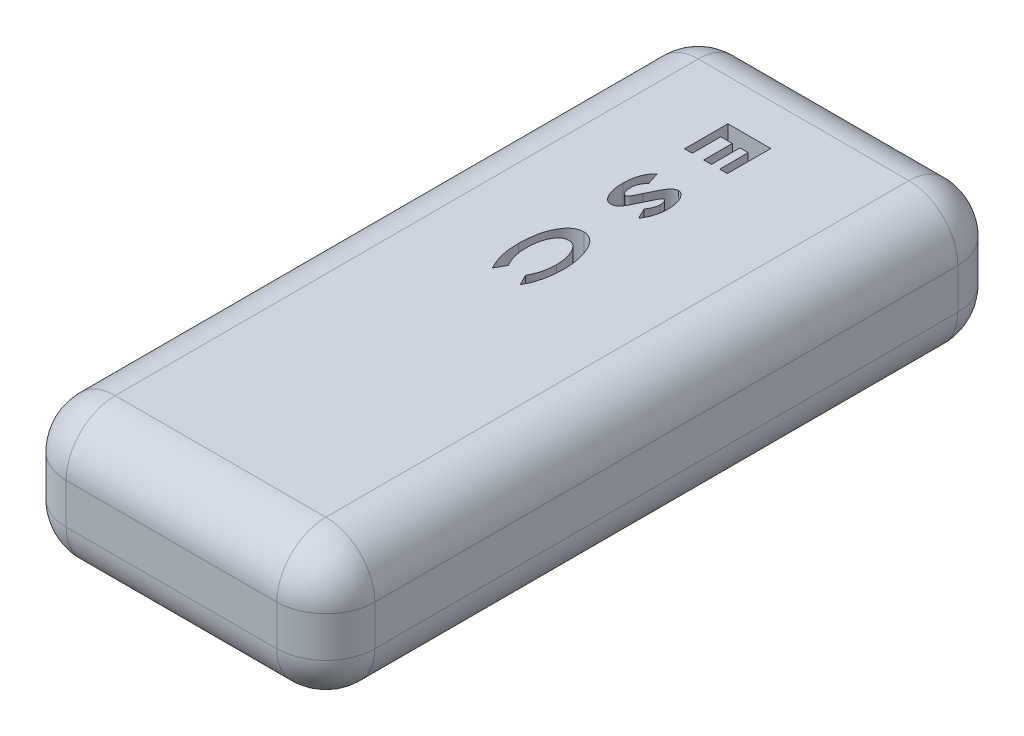
SolidWorks part; units mm, degrees
ref_plane "Front Plane" through (0, 0, 0) normal (0, 0, 1) x (1, 0, 0)
ref_plane "Top Plane" through (0, 0, 0) normal (0, 1, 0) x (1, 0, 0)
ref_plane "Right Plane" through (0, 0, 0) normal (1, 0, 0) x (0, 0, -1)
sketch "Sketch1" plane through (0, 0, 0) normal (0, 1, 0) x (1, 0, 0)
  line L1 (-56.7, 25.305) -> (-31.5, 25.305)
  line L2 (-56.7, 25.305) -> (-56.7, -30.295)
  line L3 (-56.7, -30.295) -> (-31.5, -30.295)
  line L4 (-31.5, 25.305) -> (-31.5, -30.295)
  dimension "D1" = 25.2
  dimension "D2" = 55.6
extrude "Boss-Extrude1" add sketch "Sketch1" along normal mid plane 11.3
fillet "Fillet1" radius 4 12 edges at (-44.1, 5.65, 30.295) (-31.5, 0, -25.305) (-56.7, 0, -25.305) (-44.1, -5.65, -25.305) (-44.1, 5.65, -25.305) (-56.7, -5.65, 2.495) (-56.7, 0, 30.295) (-56.7, 5.65, 2.495) (-31.5, -5.65, 2.495) (-31.5, 5.65, 2.495) (-31.5, 0, 30.295) (-44.1, -5.65, 30.295)
sketch "Sketch2" plane through (0, 5.65, 0) normal (0, 1, 0) x (1, 0, 0)
  line L0 (-46.9045, 18.6553) -> (-46.9045, -14.9982) construction
  text T0 "<b>ESC</b>" font "Century Gothic" height 3.5
extrude "Cut-Extrude1" cut sketch "Sketch2" against normal blind 5
